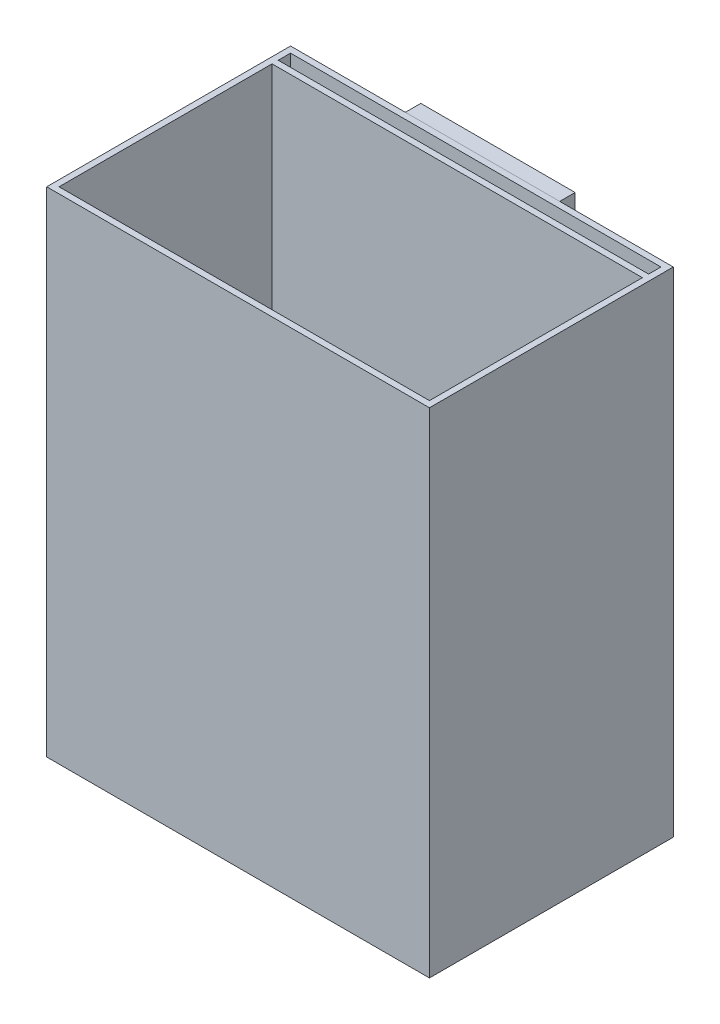
SolidWorks part; units mm, degrees
ref_plane "Front Plane" through (0, 0, 0) normal (0, 0, 1) x (1, 0, 0)
ref_plane "Top Plane" through (0, 0, 0) normal (0, 1, 0) x (1, 0, 0)
ref_plane "Right Plane" through (0, 0, 0) normal (1, 0, 0) x (0, 0, -1)
sketch "Sketch1" plane through (0, 0, 0) normal (0, 0, 1) x (1, 0, 0)
  line L1 (0, 0) -> (6200, 0)
  line L2 (0, 0) -> (0, 8000)
  line L3 (0, 8000) -> (6200, 8000)
  line L4 (6200, 0) -> (6200, 8000)
  point P5 (0, 0)
  dimension "D1" = 6200
  dimension "D2" = 8000
extrude "Boss-Extrude1" add sketch "Sketch1" along normal blind 100
sketch "Sketch2" plane through (0, 0, 100) normal (0, 0, 1) x (1, 0, 0)
  line L0 (6200, 0) -> (6200, 8000) construction
  line L1 (0, 0) -> (6200, 0)
  line L2 (0, 0) -> (0, 100)
  line L3 (0, 100) -> (6200, 100)
  line L4 (6200, 0) -> (6200, 100)
  dimension "D1" = 6200
  dimension "D2" = 100
extrude "Boss-Extrude2" add sketch "Sketch2" along normal blind 3850
sketch "Sketch3" plane through (0, 0, 3950) normal (0, 0, 1) x (1, 0, 0)
  line L1 (0, 0) -> (6200, 0)
  line L2 (0, 0) -> (0, 8000)
  line L3 (0, 8000) -> (6200, 8000)
  line L4 (6200, 0) -> (6200, 8000)
  dimension "D1" = 8000
  dimension "D2" = 6200
extrude "Boss-Extrude3" add sketch "Sketch3" against normal blind 100
sketch "Sketch4" plane through (0, 0, 0) normal (0, 0, -1) x (-1, 0, 0)
sketch "Sketch5" plane through (6200, 0, 0) normal (1, 0, 0) x (0, 0, -1)
  line L1 (-3850, 100) -> (-100, 100)
  line L2 (-3850, 100) -> (-3850, 8000)
  line L3 (-3850, 8000) -> (-100, 8000)
  line L4 (-100, 100) -> (-100, 8000)
extrude "Boss-Extrude4" add sketch "Sketch5" against normal blind 100
sketch "Sketch6" plane through (0, 0, 0) normal (-1, 0, 0) x (0, 0, 1)
  line L1 (100, 100) -> (3850, 100)
  line L2 (100, 100) -> (100, 8000)
  line L3 (100, 8000) -> (3850, 8000)
  line L4 (3850, 100) -> (3850, 8000)
extrude "Boss-Extrude5" add sketch "Sketch6" against normal blind 100
sketch "Sketch7" plane through (0, 0, 0) normal (0, 0, -1) x (-1, 0, 0)
  line L0 (-6200, 8000) -> (0, 8000) construction
  line L1 (-4350, 7990) -> (-1850, 7990)
  line L2 (-4350, 7990) -> (-4350, 6190)
  line L3 (-4350, 6190) -> (-1850, 6190)
  line L4 (-1850, 7990) -> (-1850, 6190)
  line L5 (0, 8000) -> (0, 0) construction
  line L6 (-6200, 0) -> (-6200, 8000) construction
  dimension "D1" = 10
  dimension "D2" = 1800
  dimension "D3" = 1850
  dimension "D4" = 1850
  dimension "D5" = 2500
extrude "Boss-Extrude6" add sketch "Sketch7" along normal blind 260
sketch "Sketch8" plane through (0, 0, 3850) normal (0, 0, -1) x (-1, 0, 0)
  line L0 (-6100, 8000) -> (-6100, 100) construction
  line L1 (-6100, 1600) -> (0, 1600)
  line L2 (-6100, 1600) -> (-6100, 1401.7231)
  line L3 (-6100, 1401.7231) -> (0, 1401.7231)
  line L4 (0, 1600) -> (0, 1401.7231)
  line L5 (-100, 100) -> (-6100, 100) construction
  dimension "D1" = 1500
extrude "Boss-Extrude7" add sketch "Sketch8" along normal blind 3550
sketch "Sketch9" plane through (0, 1600, 0) normal (0, 1, 0) x (1, 0, 0)
  line L0 (6100, -300) -> (6100, -3850) construction
  line L1 (100, -300) -> (6100, -300)
  line L2 (100, -300) -> (100, -400)
  line L3 (100, -400) -> (6100, -400)
  line L4 (6100, -300) -> (6100, -400)
  dimension "D1" = 100
extrude "Boss-Extrude8" add sketch "Sketch9" along normal blind 6400
